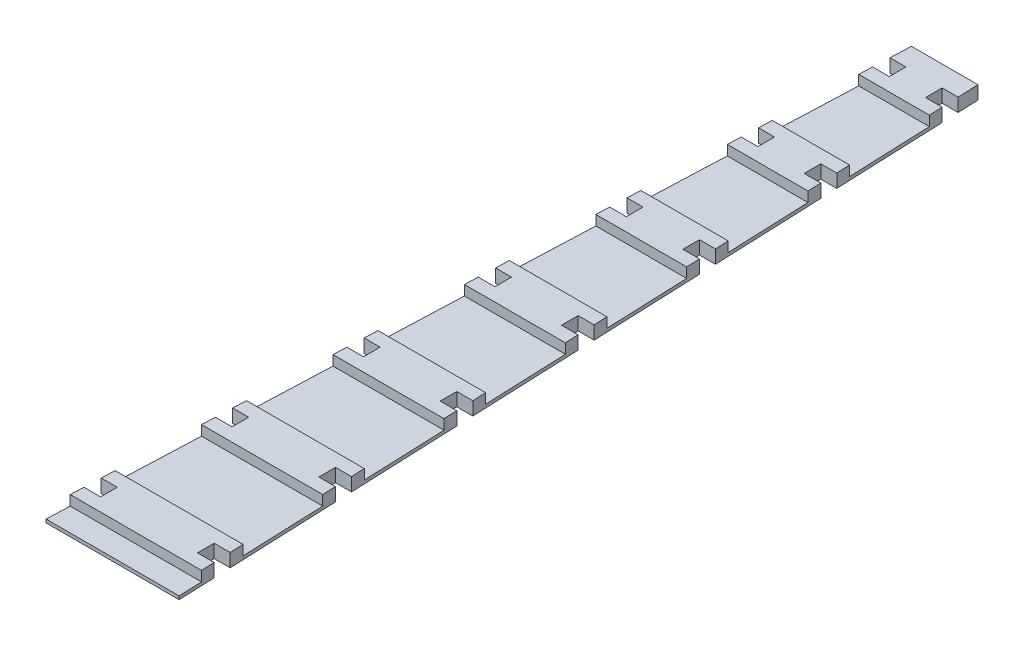
SolidWorks part; units mm, degrees
ref_plane "Front Plane" through (0, 0, 0) normal (0, 0, 1) x (1, 0, 0)
ref_plane "Top Plane" through (0, 0, 0) normal (0, 1, 0) x (1, 0, 0)
ref_plane "Right Plane" through (0, 0, 0) normal (1, 0, 0) x (0, 0, -1)
sketch "Sketch2" plane through (0, 0, 0) normal (0, 1, 0) x (1, 0, 0)
  line L0 (0, 0) -> (5, 125)
  line L1 (0, 0) -> (20, 0)
  line L5 (5, 125) -> (15, 125)
  line L6 (15, 125) -> (20, 0)
  line L7 (10, 125) -> (10, 0) construction
  line L8 (0.2192, 5.4798) -> (2.7192, 5.4798)
  line L9 (0.2192, 5.4798) -> (0.2192, 7.9798)
  line L10 (0.2192, 7.9798) -> (2.7192, 7.9798)
  line L11 (2.7192, 5.4798) -> (2.7192, 7.9798)
  line L12 (0.9786, 24.4646) -> (0.9786, 26.9646)
  line L13 (0.9786, 24.4646) -> (3.4786, 24.4646)
  line L14 (3.4786, 24.4646) -> (3.4786, 26.9646)
  line L15 (0.9786, 26.9646) -> (3.4786, 26.9646)
  line L16 (1.738, 43.4494) -> (1.738, 45.9494)
  line L17 (1.738, 43.4494) -> (4.238, 43.4494)
  line L18 (4.238, 43.4494) -> (4.238, 45.9494)
  line L19 (1.738, 45.9494) -> (4.238, 45.9494)
  line L20 (2.4974, 62.4342) -> (2.4974, 64.9342)
  line L21 (2.4974, 62.4342) -> (4.9974, 62.4342)
  line L22 (4.9974, 62.4342) -> (4.9974, 64.9342)
  line L23 (2.4974, 64.9342) -> (4.9974, 64.9342)
  line L24 (3.2568, 81.4191) -> (3.2568, 83.9191)
  line L25 (3.2568, 81.4191) -> (5.7568, 81.4191)
  line L26 (5.7568, 81.4191) -> (5.7568, 83.9191)
  line L27 (3.2568, 83.9191) -> (5.7568, 83.9191)
  line L28 (4.0162, 100.4039) -> (4.0162, 102.9039)
  line L29 (4.0162, 100.4039) -> (6.5162, 100.4039)
  line L30 (6.5162, 100.4039) -> (6.5162, 102.9039)
  line L31 (4.0162, 102.9039) -> (6.5162, 102.9039)
  line L32 (4.7755, 119.3887) -> (4.7755, 121.8887)
  line L33 (4.7755, 119.3887) -> (7.2755, 119.3887)
  line L34 (7.2755, 119.3887) -> (7.2755, 121.8887)
  line L35 (4.7755, 121.8887) -> (7.2755, 121.8887)
  line L36 (0.2192, 5.4798) -> (0.9786, 24.4646) construction
  line L37 (15.2245, 119.3887) -> (12.7245, 119.3887)
  line L38 (12.7245, 119.3887) -> (12.7245, 121.8887)
  line L39 (15.2245, 121.8887) -> (12.7245, 121.8887)
  line L40 (15.2245, 119.3887) -> (15.2245, 121.8887)
  line L41 (15.9838, 100.4039) -> (13.4838, 100.4039)
  line L42 (13.4838, 100.4039) -> (13.4838, 102.9039)
  line L43 (15.9838, 102.9039) -> (13.4838, 102.9039)
  line L44 (15.9838, 100.4039) -> (15.9838, 102.9039)
  line L45 (16.7432, 81.4191) -> (14.2432, 81.4191)
  line L46 (14.2432, 81.4191) -> (14.2432, 83.9191)
  line L47 (16.7432, 83.9191) -> (14.2432, 83.9191)
  line L48 (16.7432, 81.4191) -> (16.7432, 83.9191)
  line L49 (17.5026, 62.4342) -> (15.0026, 62.4342)
  line L50 (15.0026, 62.4342) -> (15.0026, 64.9342)
  line L51 (17.5026, 64.9342) -> (15.0026, 64.9342)
  line L52 (17.5026, 62.4342) -> (17.5026, 64.9342)
  line L53 (18.262, 43.4494) -> (15.762, 43.4494)
  line L54 (15.762, 43.4494) -> (15.762, 45.9494)
  line L55 (18.262, 45.9494) -> (15.762, 45.9494)
  line L56 (18.262, 43.4494) -> (18.262, 45.9494)
  line L57 (19.0214, 24.4646) -> (16.5214, 24.4646)
  line L58 (16.5214, 24.4646) -> (16.5214, 26.9646)
  line L59 (19.0214, 26.9646) -> (16.5214, 26.9646)
  line L60 (19.0214, 24.4646) -> (19.0214, 26.9646)
  line L61 (19.7808, 7.9798) -> (17.2808, 7.9798)
  line L62 (17.2808, 5.4798) -> (17.2808, 7.9798)
  line L63 (19.7808, 5.4798) -> (17.2808, 5.4798)
  line L64 (19.7808, 5.4798) -> (19.7808, 7.9798)
  dimension "D1" = 20
  dimension "D2" = 87.709
  dimension "D3" = 7
  dimension "D4" = 19
extrude "Boss-Extrude1" add sketch "Sketch2" along normal blind 0.5 contours L6 L63 L62 L61 L57 L58 L59 L53 L54 L55 L49 L50 L51 L45 L46 L47 L41 L42 L43 L37 L38 L39 L5 L0 L35 L34 L33 L31 L30 L29 L27 L26 L25 L23 L22 L21 L19 L18 L17
sketch "Sketch3" plane through (0, 0.5, 0) normal (0, 1, 0) x (1, 0, 0)
  line L0 (0.14, 3.5) -> (19.86, 3.5)
  line L1 (0, 0) -> (0.2192, 5.4798) construction
  line L2 (19.7808, 5.4798) -> (20, 0) construction
  line L3 (0.4, 10) -> (19.6, 10)
  line L4 (0.3192, 7.9798) -> (0.9786, 24.4646) construction
  line L5 (19.0214, 24.4646) -> (19.6808, 7.9798) construction
  line L6 (0, 0) -> (20, 0) construction
  line L7 (15.8038, 104.9039) -> (4.1962, 104.9039)
  line L8 (15.2245, 119.3887) -> (15.8838, 102.9039) construction
  line L9 (0.8986, 22.4646) -> (19.1014, 22.4646)
  line L10 (1.1586, 28.9646) -> (18.8414, 28.9646)
  line L11 (1.0786, 26.9646) -> (1.738, 43.4494) construction
  line L12 (18.262, 43.4494) -> (18.9214, 26.9646) construction
  line L13 (0.9786, 24.4646) -> (3.4786, 24.4646) construction
  line L14 (1.0786, 26.9646) -> (3.4786, 26.9646) construction
  line L15 (1.658, 41.4494) -> (18.342, 41.4494)
  line L16 (18.082, 47.9494) -> (1.918, 47.9494)
  line L17 (17.5026, 62.4342) -> (18.162, 45.9494) construction
  line L18 (1.838, 45.9494) -> (2.4974, 62.4342) construction
  line L19 (2.4174, 60.4342) -> (17.5826, 60.4342)
  line L20 (16.7432, 81.4191) -> (17.4026, 64.9342) construction
  line L21 (17.3226, 66.9342) -> (2.6774, 66.9342)
  line L22 (2.5974, 64.9342) -> (3.2568, 81.4191) construction
  line L23 (16.8232, 79.4191) -> (3.1768, 79.4191)
  line L24 (16.5632, 85.9191) -> (3.4368, 85.9191)
  line L25 (15.9838, 100.4039) -> (16.6432, 83.9191) construction
  line L26 (3.3568, 83.9191) -> (4.0162, 100.4039) construction
  line L27 (16.0638, 98.4039) -> (3.9362, 98.4039)
  line L28 (4.1162, 102.9039) -> (4.7755, 119.3887) construction
  line L29 (15.3045, 117.3887) -> (4.6955, 117.3887)
  line L30 (18.262, 43.4494) -> (15.762, 43.4494) construction
  line L31 (18.162, 45.9494) -> (15.762, 45.9494) construction
  line L32 (17.5026, 62.4342) -> (15.0026, 62.4342) construction
  line L33 (17.4026, 64.9342) -> (15.0026, 64.9342) construction
  line L34 (16.7432, 81.4191) -> (14.2432, 81.4191) construction
  line L35 (16.6432, 83.9191) -> (14.2432, 83.9191) construction
  line L36 (15.9838, 100.4039) -> (13.4838, 100.4039) construction
  line L37 (15.8838, 102.9039) -> (13.4838, 102.9039) construction
  line L38 (15.2245, 119.3887) -> (12.7245, 119.3887) construction
  line L99 (20, 0) -> (19.7808, 5.4798)
  line L100 (19.7808, 5.4798) -> (17.2808, 5.4798)
  line L101 (17.2808, 5.4798) -> (17.2808, 7.9798)
  line L102 (17.2808, 7.9798) -> (19.6808, 7.9798)
  line L103 (19.6808, 7.9798) -> (19.0214, 24.4646)
  line L104 (19.0214, 24.4646) -> (16.5214, 24.4646)
  line L105 (16.5214, 24.4646) -> (16.5214, 26.9646)
  line L106 (16.5214, 26.9646) -> (18.9214, 26.9646)
  line L107 (18.9214, 26.9646) -> (18.262, 43.4494)
  line L108 (18.262, 43.4494) -> (15.762, 43.4494)
  line L109 (15.762, 43.4494) -> (15.762, 45.9494)
  line L110 (15.762, 45.9494) -> (18.162, 45.9494)
  line L111 (18.162, 45.9494) -> (17.5026, 62.4342)
  line L112 (17.5026, 62.4342) -> (15.0026, 62.4342)
  line L113 (15.0026, 62.4342) -> (15.0026, 64.9342)
  line L114 (15.0026, 64.9342) -> (17.4026, 64.9342)
  line L115 (17.4026, 64.9342) -> (16.7432, 81.4191)
  line L116 (16.7432, 81.4191) -> (14.2432, 81.4191)
  line L117 (14.2432, 81.4191) -> (14.2432, 83.9191)
  line L118 (14.2432, 83.9191) -> (16.6432, 83.9191)
  line L119 (16.6432, 83.9191) -> (15.9838, 100.4039)
  line L120 (15.9838, 100.4039) -> (13.4838, 100.4039)
  line L121 (13.4838, 100.4039) -> (13.4838, 102.9039)
  line L122 (13.4838, 102.9039) -> (15.8838, 102.9039)
  line L123 (15.8838, 102.9039) -> (15.2245, 119.3887)
  line L124 (15.2245, 119.3887) -> (12.7245, 119.3887)
  line L125 (12.7245, 119.3887) -> (12.7245, 121.8887)
  line L126 (12.7245, 121.8887) -> (15.1245, 121.8887)
  line L127 (15.1245, 121.8887) -> (15, 125)
  line L128 (15, 125) -> (5, 125)
  line L129 (5, 125) -> (4.8755, 121.8887)
  line L130 (4.8755, 121.8887) -> (7.2755, 121.8887)
  line L131 (7.2755, 121.8887) -> (7.2755, 119.3887)
  line L132 (7.2755, 119.3887) -> (4.7755, 119.3887)
  line L133 (4.7755, 119.3887) -> (4.1162, 102.9039)
  line L134 (4.1162, 102.9039) -> (6.5162, 102.9039)
  line L135 (6.5162, 102.9039) -> (6.5162, 100.4039)
  line L136 (6.5162, 100.4039) -> (4.0162, 100.4039)
  line L137 (4.0162, 100.4039) -> (3.3568, 83.9191)
  line L138 (3.3568, 83.9191) -> (5.7568, 83.9191)
  line L139 (5.7568, 83.9191) -> (5.7568, 81.4191)
  line L140 (5.7568, 81.4191) -> (3.2568, 81.4191)
  line L141 (3.2568, 81.4191) -> (2.5974, 64.9342)
  line L142 (2.5974, 64.9342) -> (4.9974, 64.9342)
  line L143 (4.9974, 64.9342) -> (4.9974, 62.4342)
  line L144 (4.9974, 62.4342) -> (2.4974, 62.4342)
  line L145 (2.4974, 62.4342) -> (1.838, 45.9494)
  line L146 (1.838, 45.9494) -> (4.238, 45.9494)
  line L147 (4.238, 45.9494) -> (4.238, 43.4494)
  line L148 (4.238, 43.4494) -> (1.738, 43.4494)
  line L149 (1.738, 43.4494) -> (1.0786, 26.9646)
  line L150 (1.0786, 26.9646) -> (3.4786, 26.9646)
  line L151 (3.4786, 26.9646) -> (3.4786, 24.4646)
  line L152 (3.4786, 24.4646) -> (0.9786, 24.4646)
  line L153 (0.9786, 24.4646) -> (0.3192, 7.9798)
  line L154 (0.3192, 7.9798) -> (2.7192, 7.9798)
  line L155 (2.7192, 7.9798) -> (2.7192, 5.4798)
  line L156 (2.7192, 5.4798) -> (0.2192, 5.4798)
  line L157 (0.2192, 5.4798) -> (0, 0)
  line L158 (0, 0) -> (20, 0)
  line L159 (20, 0) -> (19.7808, 5.4798)
  line L160 (19.7808, 5.4798) -> (17.2808, 5.4798)
  line L161 (17.2808, 5.4798) -> (17.2808, 7.9798)
  line L162 (17.2808, 7.9798) -> (19.6808, 7.9798)
  line L163 (19.6808, 7.9798) -> (19.0214, 24.4646)
  line L164 (19.0214, 24.4646) -> (16.5214, 24.4646)
  line L165 (16.5214, 24.4646) -> (16.5214, 26.9646)
  line L166 (16.5214, 26.9646) -> (18.9214, 26.9646)
  line L167 (18.9214, 26.9646) -> (18.262, 43.4494)
  line L168 (18.262, 43.4494) -> (15.762, 43.4494)
  line L169 (15.762, 43.4494) -> (15.762, 45.9494)
  line L170 (15.762, 45.9494) -> (18.162, 45.9494)
  line L171 (18.162, 45.9494) -> (17.5026, 62.4342)
  line L172 (17.5026, 62.4342) -> (15.0026, 62.4342)
  line L173 (15.0026, 62.4342) -> (15.0026, 64.9342)
  line L174 (15.0026, 64.9342) -> (17.4026, 64.9342)
  line L175 (17.4026, 64.9342) -> (16.7432, 81.4191)
  line L176 (16.7432, 81.4191) -> (14.2432, 81.4191)
  line L177 (14.2432, 81.4191) -> (14.2432, 83.9191)
  line L178 (14.2432, 83.9191) -> (16.6432, 83.9191)
  line L179 (16.6432, 83.9191) -> (15.9838, 100.4039)
  line L180 (15.9838, 100.4039) -> (13.4838, 100.4039)
  line L181 (13.4838, 100.4039) -> (13.4838, 102.9039)
  line L182 (13.4838, 102.9039) -> (15.8838, 102.9039)
  line L183 (15.8838, 102.9039) -> (15.2245, 119.3887)
  line L184 (15.2245, 119.3887) -> (12.7245, 119.3887)
  line L185 (12.7245, 119.3887) -> (12.7245, 121.8887)
  line L186 (12.7245, 121.8887) -> (15.1245, 121.8887)
  line L187 (15.1245, 121.8887) -> (15, 125)
  line L188 (15, 125) -> (5, 125)
  line L189 (5, 125) -> (4.8755, 121.8887)
  line L190 (4.8755, 121.8887) -> (7.2755, 121.8887)
  line L191 (7.2755, 121.8887) -> (7.2755, 119.3887)
  line L192 (7.2755, 119.3887) -> (4.7755, 119.3887)
  line L193 (4.7755, 119.3887) -> (4.1162, 102.9039)
  line L194 (4.1162, 102.9039) -> (6.5162, 102.9039)
  line L195 (6.5162, 102.9039) -> (6.5162, 100.4039)
  line L196 (6.5162, 100.4039) -> (4.0162, 100.4039)
  line L197 (4.0162, 100.4039) -> (3.3568, 83.9191)
  line L198 (3.3568, 83.9191) -> (5.7568, 83.9191)
  line L199 (5.7568, 83.9191) -> (5.7568, 81.4191)
  line L200 (5.7568, 81.4191) -> (3.2568, 81.4191)
  line L201 (3.2568, 81.4191) -> (2.5974, 64.9342)
  line L202 (2.5974, 64.9342) -> (4.9974, 64.9342)
  line L203 (4.9974, 64.9342) -> (4.9974, 62.4342)
  line L204 (4.9974, 62.4342) -> (2.4974, 62.4342)
  line L205 (2.4974, 62.4342) -> (1.838, 45.9494)
  line L206 (1.838, 45.9494) -> (4.238, 45.9494)
  line L207 (4.238, 45.9494) -> (4.238, 43.4494)
  line L208 (4.238, 43.4494) -> (1.738, 43.4494)
  line L209 (1.738, 43.4494) -> (1.0786, 26.9646)
  line L210 (1.0786, 26.9646) -> (3.4786, 26.9646)
  line L211 (3.4786, 26.9646) -> (3.4786, 24.4646)
  line L212 (3.4786, 24.4646) -> (0.9786, 24.4646)
  line L213 (0.9786, 24.4646) -> (0.3192, 7.9798)
  line L214 (0.3192, 7.9798) -> (2.7192, 7.9798)
  line L215 (2.7192, 7.9798) -> (2.7192, 5.4798)
  line L216 (2.7192, 5.4798) -> (0.2192, 5.4798)
  line L217 (0.2192, 5.4798) -> (0, 0)
  line L218 (0, 0) -> (20, 0)
  point P68 (16.2026, 64.9342)
  point P79 (13.9745, 119.3887)
  dimension "D1" = 3.5
  dimension "D2" = 6.5
  dimension "D3" = 2
  dimension "D4" = 2
  dimension "D5" = 2
  dimension "D6" = 2
  dimension "D7" = 2
  dimension "D8" = 2
  dimension "D9" = 2
  dimension "D10" = 2
  dimension "D11" = 2
  dimension "D12" = 2
  dimension "D13" = 2
  dimension "D14" = 0
extrude "Boss-Extrude2" add sketch "Sketch3" along normal blind 1.5 contours L216 L217 L0 L159 L160 L161 L162 L163 L3 L213 L214 L215 | L212 L213 L9 L163 L164 L165 L166 L167 L10 L209 L210 L211 | L208 L209 L15 L167 L168 L169 L170 L171 L16 L205 L206 L207 | L204 L205 L19 L171 L172 L173 L174 L175 L21 L201 L202 L203 | L200 L201 L23 L175 L176 L177 L178 L179 L24 L197 L198 L199 | L196 L197 L27 L179 L180 L181 L182 L183 L7 L193 L194 L195 | L192 L193 L29 L183 L184 L185 L186 L187 L188 L189 L190 L191
